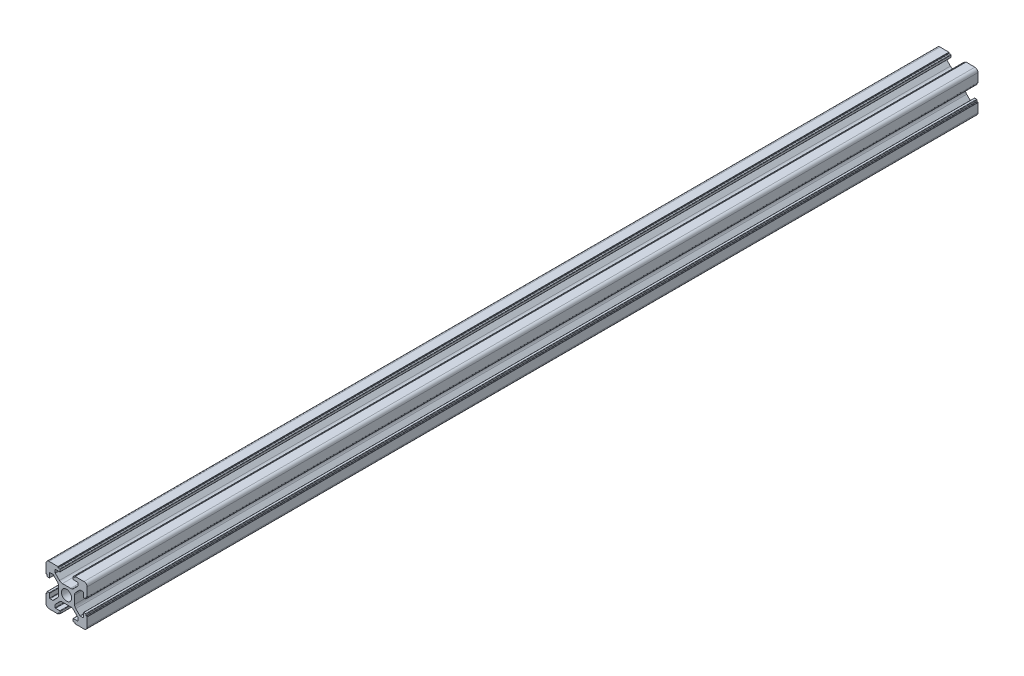
SolidWorks part; units mm, degrees
material "6063-T5"
ref_plane "Front Plane" through (0, 0, 0) normal (0, 0, 1) x (1, 0, 0)
ref_plane "Top Plane" through (0, 0, 0) normal (0, 1, 0) x (1, 0, 0)
ref_plane "Right Plane" through (0, 0, 0) normal (1, 0, 0) x (0, 0, -1)
sketch "Sketch1" plane through (0, 0, 0) normal (0, 0, -1) x (1, 0, 0)
  line L0 (1.5, 0) -> (5.8, 0)
  line L1 (20, 1.5) -> (20, 5.8)
  line L2 (18.5, 20) -> (14.2, 20)
  line L3 (0, 18.5) -> (0, 14.2)
  line L4 (14.2, 0) -> (18.5, 0)
  line L5 (13.3, 18.2) -> (15.3, 18.2)
  line L6 (20, 14.2) -> (20, 18.5)
  line L7 (0, 5.8) -> (0, 1.5)
  line L8 (6.7, 18.2) -> (4.7, 18.2)
  line L9 (1.8, 13.3) -> (1.8, 15.3)
  line L10 (19.3, 13.1) -> (18.4, 13.1)
  line L11 (19.3, 6.9) -> (18.4, 6.9)
  line L12 (6.9, 19.3) -> (6.9, 18.4)
  line L13 (13.1, 19.3) -> (13.1, 18.4)
  line L14 (0.7, 13.1) -> (1.6, 13.1)
  line L15 (0.7, 6.9) -> (1.6, 6.9)
  line L16 (13.4251, 14.4858) -> (15.4121, 16.4728)
  line L17 (14.4858, 13.4251) -> (16.4728, 15.4121)
  line L18 (14.4858, 6.5749) -> (16.4728, 4.5879)
  line L19 (13.4251, 5.5142) -> (15.4121, 3.5272)
  line L20 (6.5749, 5.5142) -> (4.5879, 3.5272)
  line L21 (5.5142, 6.5749) -> (3.5272, 4.5879)
  line L22 (5.5142, 13.4251) -> (3.5272, 15.4121)
  line L23 (6.5749, 14.4858) -> (4.5879, 16.4728)
  line L24 (6.9, 0.7) -> (6.9, 1.6)
  line L25 (13.1, 0.7) -> (13.1, 1.6)
  line L26 (5.8, 20) -> (1.5, 20)
  line L27 (1.8, 6.7) -> (1.8, 4.7)
  line L28 (6.7, 1.8) -> (4.7, 1.8)
  line L29 (13.3, 1.8) -> (15.3, 1.8)
  line L30 (18.2, 13.3) -> (18.2, 15.3)
  line L31 (18.2, 6.7) -> (18.2, 4.7)
  line L32 (2, 4.5) -> (3.3151, 4.5)
  line L33 (2, 15.5) -> (3.3151, 15.5)
  line L34 (4.5, 18) -> (4.5, 16.6849)
  line L35 (15.5, 18) -> (15.5, 16.6849)
  line L36 (18, 15.5) -> (16.6849, 15.5)
  line L37 (4.5, 2) -> (4.5, 3.3151)
  line L38 (15.5, 2) -> (15.5, 3.3151)
  line L39 (18, 4.5) -> (16.6849, 4.5)
  line L40 (7.9891, 13.9) -> (12.0109, 13.9)
  line L41 (7.9891, 6.1) -> (12.0109, 6.1)
  line L42 (13.9, 12.0109) -> (13.9, 7.9891)
  line L43 (6.1, 12.0109) -> (6.1, 7.9891)
  line L44 (19.5, 6.7) -> (19.5, 6.1)
  line L45 (5.9, 19.9) -> (5.9, 19.7)
  line L46 (6.1, 19.5) -> (6.7, 19.5)
  line L47 (14.1, 19.9) -> (14.1, 19.7)
  line L48 (13.9, 19.5) -> (13.3, 19.5)
  line L49 (0.1, 14.1) -> (0.3, 14.1)
  line L50 (0.5, 13.9) -> (0.5, 13.3)
  line L51 (0.1, 5.9) -> (0.3, 5.9)
  line L52 (0.5, 6.1) -> (0.5, 6.7)
  line L53 (19.9, 14.1) -> (19.7, 14.1)
  line L54 (19.5, 13.9) -> (19.5, 13.3)
  line L55 (19.7, 5.9) -> (19.9, 5.9)
  line L56 (14.1, 0.1) -> (14.1, 0.3)
  line L57 (13.9, 0.5) -> (13.3, 0.5)
  line L58 (6.7, 0.5) -> (6.1, 0.5)
  line L59 (5.9, 0.3) -> (5.9, 0.1)
  circle A0 centre (10, 10) radius 2.5
  arc A1 (18.5, 0) -> (20, 1.5) centre (18.5, 1.5) ccw
  arc A2 (1.5, 0) -> (0, 1.5) centre (1.5, 1.5) cw
  arc A3 (20, 18.5) -> (18.5, 20) centre (18.5, 18.5) ccw
  arc A4 (1.5, 20) -> (0, 18.5) centre (1.5, 18.5) ccw
  arc A5 (12.0109, 6.1) -> (13.4251, 5.5142) centre (12.0109, 4.1) cw
  arc A6 (13.9, 7.9891) -> (14.4858, 6.5749) centre (15.9, 7.9891) ccw
  arc A7 (13.9, 12.0109) -> (14.4858, 13.4251) centre (15.9, 12.0109) cw
  arc A8 (12.0109, 13.9) -> (13.4251, 14.4858) centre (12.0109, 15.9) ccw
  arc A9 (7.9891, 13.9) -> (6.5749, 14.4858) centre (7.9891, 15.9) cw
  arc A10 (6.1, 7.9891) -> (5.5142, 6.5749) centre (4.1, 7.9891) cw
  arc A11 (6.1, 12.0109) -> (5.5142, 13.4251) centre (4.1, 12.0109) ccw
  arc A12 (13.1, 1.6) -> (13.3, 1.8) centre (13.3, 1.6) cw
  arc A13 (6.9, 1.6) -> (6.7, 1.8) centre (6.7, 1.6) ccw
  arc A14 (6.1, 0.5) -> (5.9, 0.3) centre (6.1, 0.3) ccw
  arc A15 (6.7, 0.5) -> (6.9, 0.7) centre (6.7, 0.7) ccw
  arc A16 (1.6, 6.9) -> (1.8, 6.7) centre (1.6, 6.7) cw
  arc A17 (0.5, 6.7) -> (0.7, 6.9) centre (0.7, 6.7) cw
  arc A18 (0.5, 13.3) -> (0.7, 13.1) centre (0.7, 13.3) ccw
  arc A19 (1.6, 13.1) -> (1.8, 13.3) centre (1.6, 13.3) ccw
  arc A20 (6.7, 19.5) -> (6.9, 19.3) centre (6.7, 19.3) cw
  arc A21 (6.9, 18.4) -> (6.7, 18.2) centre (6.7, 18.4) cw
  arc A22 (13.1, 18.4) -> (13.3, 18.2) centre (13.3, 18.4) ccw
  arc A23 (13.3, 19.5) -> (13.1, 19.3) centre (13.3, 19.3) ccw
  arc A24 (18.4, 13.1) -> (18.2, 13.3) centre (18.4, 13.3) cw
  arc A25 (19.5, 13.3) -> (19.3, 13.1) centre (19.3, 13.3) cw
  arc A26 (19.5, 6.7) -> (19.3, 6.9) centre (19.3, 6.7) ccw
  arc A27 (14.1, 0.3) -> (13.9, 0.5) centre (13.9, 0.3) ccw
  arc A28 (19.5, 6.1) -> (19.7, 5.9) centre (19.7, 6.1) ccw
  arc A29 (5.9, 19.7) -> (6.1, 19.5) centre (6.1, 19.7) ccw
  arc A30 (14.1, 19.7) -> (13.9, 19.5) centre (13.9, 19.7) cw
  arc A31 (19.7, 14.1) -> (19.5, 13.9) centre (19.7, 13.9) ccw
  arc A32 (13.3, 0.5) -> (13.1, 0.7) centre (13.3, 0.7) cw
  arc A33 (0.3, 14.1) -> (0.5, 13.9) centre (0.3, 13.9) cw
  arc A34 (0.3, 5.9) -> (0.5, 6.1) centre (0.3, 6.1) ccw
  arc A35 (0, 5.8) -> (0.1, 5.9) centre (0.1, 5.8) cw
  arc A36 (5.9, 0.1) -> (5.8, 0) centre (5.8, 0.1) cw
  arc A37 (14.1, 0.1) -> (14.2, 0) centre (14.2, 0.1) ccw
  arc A38 (19.9, 5.9) -> (20, 5.8) centre (19.9, 5.8) cw
  arc A39 (20, 14.2) -> (19.9, 14.1) centre (19.9, 14.2) cw
  arc A40 (14.2, 20) -> (14.1, 19.9) centre (14.2, 19.9) ccw
  arc A41 (5.8, 20) -> (5.9, 19.9) centre (5.8, 19.9) cw
  arc A42 (0, 14.2) -> (0.1, 14.1) centre (0.1, 14.2) ccw
  arc A43 (18.4, 6.9) -> (18.2, 6.7) centre (18.4, 6.7) ccw
  arc A44 (1.8, 15.3) -> (2, 15.5) centre (2, 15.3) cw
  arc A45 (1.8, 4.7) -> (2, 4.5) centre (2, 4.7) ccw
  arc A46 (4.7, 1.8) -> (4.5, 2) centre (4.7, 2) cw
  arc A47 (15.3, 1.8) -> (15.5, 2) centre (15.3, 2) ccw
  arc A48 (18.2, 4.7) -> (18, 4.5) centre (18, 4.7) cw
  arc A49 (18.2, 15.3) -> (18, 15.5) centre (18, 15.3) ccw
  arc A50 (15.3, 18.2) -> (15.5, 18) centre (15.3, 18) cw
  arc A51 (4.7, 18.2) -> (4.5, 18) centre (4.7, 18) ccw
  arc A52 (7.9891, 6.1) -> (6.5749, 5.5142) centre (7.9891, 4.1) ccw
  arc A53 (3.3151, 15.5) -> (3.5272, 15.4121) centre (3.3151, 15.2) cw
  arc A54 (4.5, 16.6849) -> (4.5879, 16.4728) centre (4.8, 16.6849) ccw
  arc A55 (15.5, 16.6849) -> (15.4121, 16.4728) centre (15.2, 16.6849) cw
  arc A56 (16.6849, 15.5) -> (16.4728, 15.4121) centre (16.6849, 15.2) ccw
  arc A57 (16.6849, 4.5) -> (16.4728, 4.5879) centre (16.6849, 4.8) cw
  arc A58 (15.5, 3.3151) -> (15.4121, 3.5272) centre (15.2, 3.3151) ccw
  arc A59 (4.5, 3.3151) -> (4.5879, 3.5272) centre (4.8, 3.3151) cw
  arc A60 (3.3151, 4.5) -> (3.5272, 4.5879) centre (3.3151, 4.8) ccw
  point P67 (0, 0)
  point P125 (14.1, 19.5)
extrude "Boss-Extrude1" add sketch "Sketch1" along normal blind 434 contours L23 A54 L34 A51 L8 A21 L12 A20 L46 A29 L45 A41 L26 A4 L3 A42 L49 A33 L50 A18 L14 A19 L9 A44 L33 A53 L22 A11 L43 A10 L21 A60 L32 A45 L27 A16 L15 A17 L52 A34 L51 A35 L7 A2 L0 A36 L59 A14 L58 A15 L24 A13 L28 A46 L37 A59 L20 A52 L41 A5 L19 A58 L38 A47 L29 A12 L25 A32 L57 A27 L56 A37 L4 A1 L1 A38 L55 A28 L44 A26 L11 A43 L31 A48 L39 A57 L18 A6 L42 A7 L17 A56 L36 A49 L30 A24 L10 A25 L54 A31 L53 A39 L6 A3 L2 A40 L47 A30 L48 A23 L13 A22 L5 A50 L35 A55 L16 A8 L40 A9 | A0
